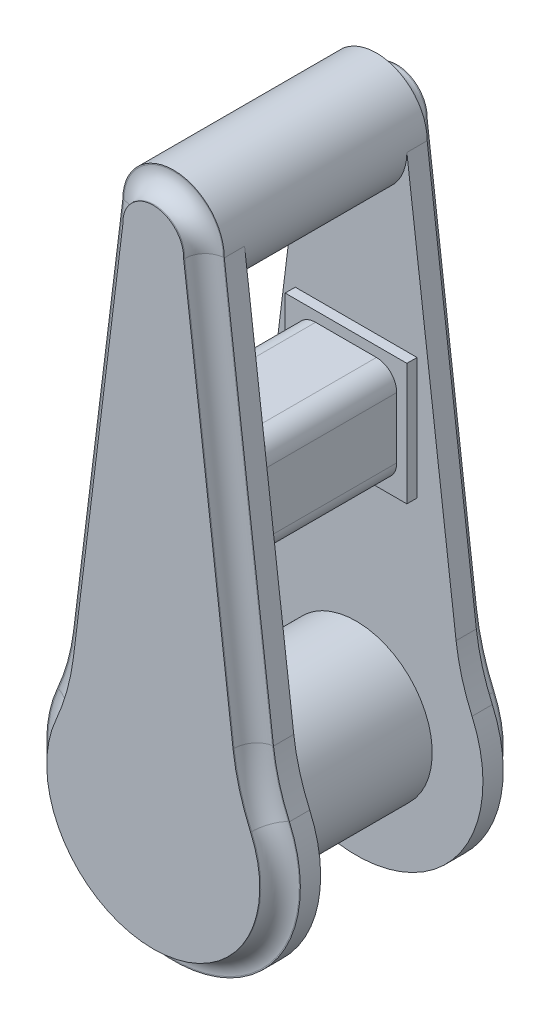
SolidWorks part; units mm, degrees
material "AISI 4340 Steel, annealed"
ref_plane "Ön Düzlem" through (0, 0, 0) normal (0, 0, 1) x (1, 0, 0)
ref_plane "Üst Düzlem" through (0, 0, 0) normal (0, 1, 0) x (1, 0, 0)
ref_plane "Sağ Düzlem" through (0, 0, 0) normal (1, 0, 0) x (0, 0, -1)
sketch "Çizim1" plane through (0, 0, 0) normal (0, 0, 1) x (1, 0, 0)
  circle A0 centre (0, 0) radius 75
  circle A1 centre (0, 500) radius 50
  dimension "D1" = 150
extrude "Yükseklik-Ekstrüzyon1" add sketch "Çizim1" along normal blind 180
sketch "Çizim2" plane through (0, 0, 0) normal (0, 0, 1) x (1, 0, 0)
  line L0 (50, 500) -> (98.4957, 107.4767)
  line L1 (0, 500) -> (0, 0) construction
  line L2 (-50, 500) -> (-98.4957, 107.4767)
  arc A0 (-114.2256, 50.7692) -> (114.2256, 50.7692) centre (0, 0) ccw
  arc A1 (98.4957, 107.4767) -> (114.2256, 50.7692) centre (296.9865, 132) ccw
  circle A2 centre (0, 500) radius 50 construction
  arc A3 (-98.4957, 107.4767) -> (-114.2256, 50.7692) centre (-296.9865, 132) cw
  circle A4 centre (0, 500) radius 50
  arc A5 (50, 500) -> (-50, 500) centre (0, 500) ccw
  dimension "D1" = 250
  dimension "D2" = 400
  dimension "D3" = 132
  dimension "D5" = 392.5233
  dimension "D4" = 0
extrude "Yükseklik-Ekstrüzyon2" add sketch "Çizim2" against normal blind 20
sketch "Çizim3" plane through (0, 0, -20) normal (0, 0, -1) x (-1, 0, 0)
  line L6 (-29.9807, 498.9251) -> (-78.6466, 105.0244)
  line L7 (78.6466, 105.0244) -> (29.9807, 498.9251)
  line L8 (-29.9807, 498.9251) -> (-78.6466, 105.0244)
  line L9 (78.6466, 105.0244) -> (29.9807, 498.9251)
  arc A12 (29.9807, 498.9251) -> (-29.9807, 498.9251) centre (0, 500) ccw
  arc A13 (-95.9495, 42.6462) -> (-78.6466, 105.0244) centre (-296.9865, 132) ccw
  arc A14 (-95.9495, 42.6462) -> (95.9495, 42.6462) centre (0, 0) ccw
  arc A15 (78.6466, 105.0244) -> (95.9495, 42.6462) centre (296.9865, 132) ccw
  arc A16 (29.9807, 498.9251) -> (-29.9807, 498.9251) centre (0, 500) ccw
  arc A17 (-95.9495, 42.6462) -> (-78.6466, 105.0244) centre (-296.9865, 132) ccw
  arc A18 (-95.9495, 42.6462) -> (95.9495, 42.6462) centre (0, 0) ccw
  arc A19 (78.6466, 105.0244) -> (95.9495, 42.6462) centre (296.9865, 132) ccw
  dimension "D1" = 20
extrude "Yükseklik-Ekstrüzyon3" add sketch "Çizim3" along normal blind 20
fillet "Radyus1" radius 19 6 edges at (54.3137, 301.9748, -20) (84.9912, 73.1954, -20) (0, -105, -20) (-84.9912, 73.1954, -20) (0, 530, -20) (-54.3137, 301.9748, -20)
ref_plane "Düzlem1" through (0, 0, 80) normal (0, 0, 1) x (1, 0, 0)
mirror "Aynalama1" about plane through (0, 0, 80) normal (0, 0, 1) of "Yükseklik-Ekstrüzyon2", "Radyus1", "Yükseklik-Ekstrüzyon3"
sketch "Çizim4" plane through (0, 0, 160) normal (0, 0, -1) x (-1, 0, 0)
  line L1 (-60, 210) -> (60, 210)
  line L2 (-60, 210) -> (-60, 330)
  line L3 (-60, 330) -> (60, 330)
  line L4 (60, 210) -> (60, 330)
  line L5 (-60, 210) -> (60, 330) construction
  line L6 (-60, 330) -> (60, 210) construction
  point P0 (0, 270)
  dimension "D1" = 120
  dimension "D2" = 120
  dimension "D3" = 270
extrude "Yükseklik-Ekstrüzyon4" add sketch "Çizim4" along normal blind 10
mirror "Aynalama2" about plane through (0, 0, 80) normal (0, 0, 1) of "Yükseklik-Ekstrüzyon4"
sketch "Çizim6" plane through (0, 0, 150) normal (0, 0, -1) x (-1, 0, 0)
  line L8 (50, 220) -> (50, 320)
  line L9 (50, 320) -> (-50, 320)
  line L10 (-50, 320) -> (-50, 220)
  line L11 (-50, 220) -> (50, 220)
  line L12 (50, 220) -> (50, 320)
  line L13 (50, 320) -> (-50, 320)
  line L14 (-50, 320) -> (-50, 220)
  line L15 (-50, 220) -> (50, 220)
  dimension "D1" = 10
extrude "Yükseklik-Ekstrüzyon5" add sketch "Çizim6" along normal up to next
fillet "Radyus2" radius 20 4 edges at (50, 320, 80) (50, 220, 80) (-50, 220, 80) (-50, 320, 80)
